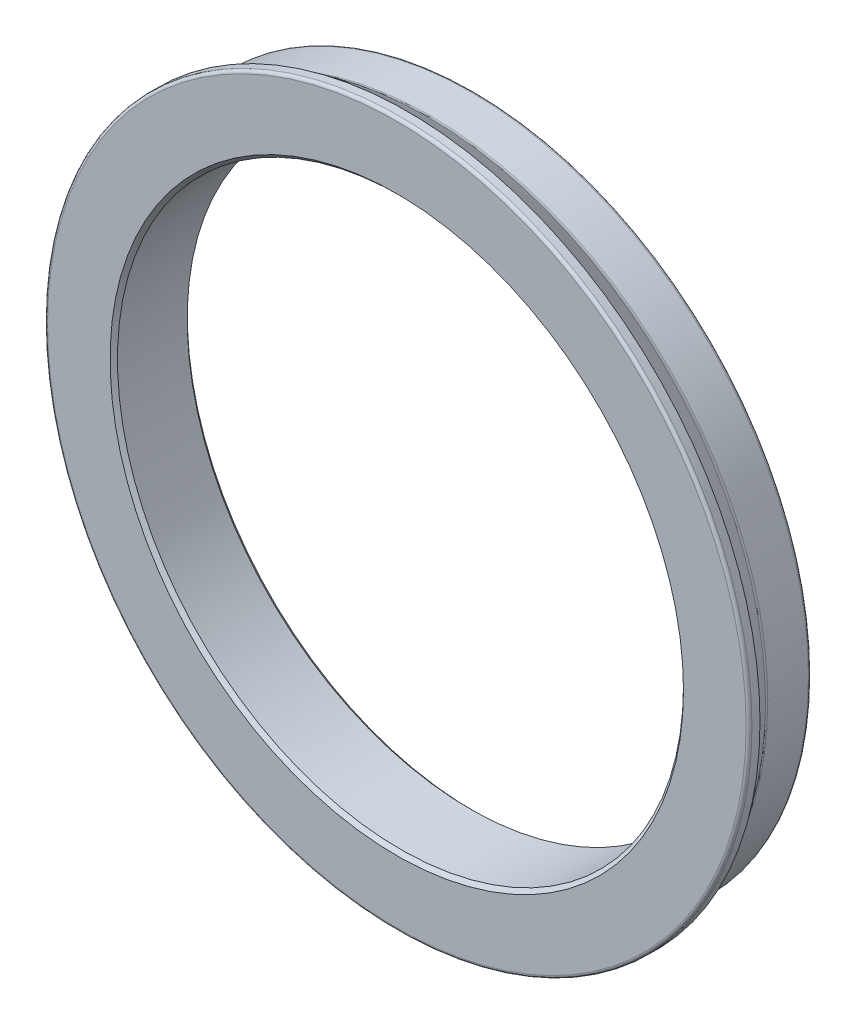
SolidWorks part; units mm, degrees
material "PB01 (C90710) Bronze"
ref_plane "Front Plane" through (0, 0, 0) normal (0, 0, 1) x (1, 0, 0)
ref_plane "Top Plane" through (0, 0, 0) normal (0, 1, 0) x (1, 0, 0)
ref_plane "Right Plane" through (0, 0, 0) normal (1, 0, 0) x (0, 0, -1)
sketch "Sketch1" plane through (0, 0, 0) normal (1, 0, 0) x (0, 0, -1)
  line L0 (0, 0) -> (41.4438, 0) construction
  line L1 (0, 39.05) -> (0.5, 38.55)
  line L2 (0.4, 47.975) -> (1.5, 47.975)
  line L3 (0, 47.575) -> (0, 39.05)
  line L4 (0.5, 38.55) -> (10, 38.55)
  line L6 (10.5, 39.05) -> (10, 38.55)
  line L8 (1.5, 47.975) -> (4.0914, 46.124)
  line L9 (4.5564, 45.975) -> (10.1, 45.975)
  line L10 (10.5, 45.575) -> (10.5, 39.05)
  arc A0 (10.5, 45.575) -> (10.1, 45.975) centre (10.1, 45.575) ccw
  arc A1 (0, 47.575) -> (0.4, 47.975) centre (0.4, 47.575) cw
  arc A2 (4.0914, 46.124) -> (4.5564, 45.975) centre (4.5564, 46.775) ccw
  point P5 (0, 38.55)
  point P6 (5, 48.2)
  point P17 (10.5, 38.55)
  point P20 (4.3, 45.975)
  dimension "D7" = 6.2
  dimension "D8" = 0.4
  dimension "D9" = 0.4
  dimension "D10" = 0.8
  dimension "D1" = 77.1
  dimension "D2" = 95.95
  dimension "D3" = 1.5
  dimension "D4" = 91.95
  dimension "D5" = 10.5
revolve "Revolve1" add sketch "Sketch1" angle 360 about L0
